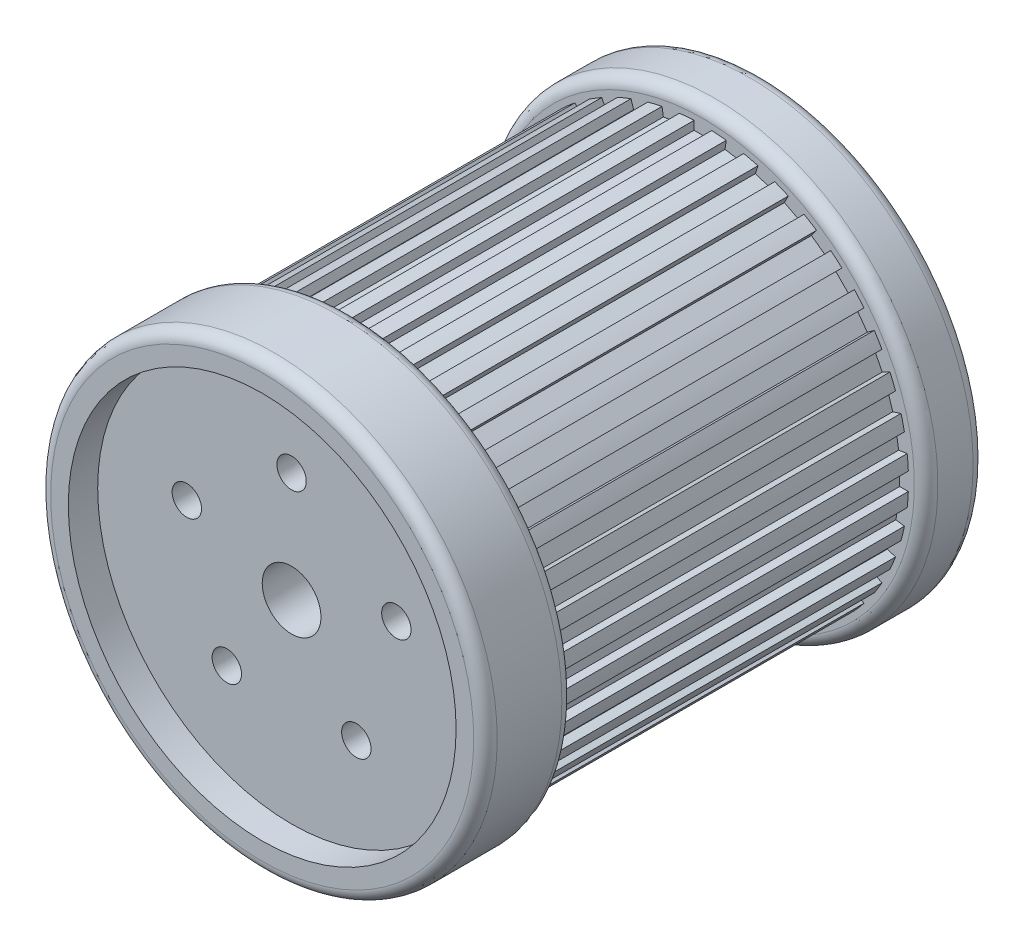
SolidWorks part; units mm, degrees
ref_plane "Front Plane" through (0, 0, 0) normal (0, 0, 1) x (1, 0, 0)
ref_plane "Top Plane" through (0, 0, 0) normal (0, 1, 0) x (1, 0, 0)
ref_plane "Right Plane" through (0, 0, 0) normal (1, 0, 0) x (0, 0, -1)
sketch "Sketch1" plane through (0, 0, 0) normal (1, 0, 0) x (0, 0, -1)
  line L0 (-51.6456, 0) -> (51.6456, 0) construction
  line L1 (-52.5, 35) -> (-52.5, -35) construction
  line L2 (-42.5, 25) -> (42.5, 25) construction
  line L3 (-42.5, 25) -> (-42.5, -25) construction
  line L4 (-42.5, -25) -> (42.5, -25) construction
  line L5 (42.5, 25) -> (42.5, -25) construction
  line L6 (-42.5, 25) -> (42.5, -25) construction
  line L7 (-42.5, -25) -> (42.5, 25) construction
  line L8 (-52.5, -35) -> (52.5, -35) construction
  line L9 (52.5, 35) -> (52.5, -35) construction
  line L10 (-52.5, 35) -> (52.5, 35) construction
  line L11 (-27.5, 0) -> (-27.5, -35)
  line L12 (-27.5, -35) -> (52.5, -35)
  line L13 (-27.5, 0) -> (-17.5, 0)
  line L14 (-17.5, 0) -> (-17.5, -25)
  line L15 (-17.5, -25) -> (52.5, -25)
  line L16 (52.5, -25) -> (52.5, -35)
  point P0 (0, 0)
  point P4 (0, 0)
  dimension "D2" = 50
  dimension "D3" = 80
  dimension "D4" = 50
  dimension "D5" = 85
  dimension "D1" = 10
revolve "Revolve1" add sketch "Sketch1" angle 360 about L0
sketch "Sketch2" plane through (0, 0, 17.5) normal (0, 0, -1) x (-1, 0, 0)
  circle A0 centre (0, 0) radius 5
  circle A1 centre (0, 0) radius 18.75 construction
  circle A2 centre (0, 18.75) radius 2.5
  circle A3 centre (17.8323, 5.7941) radius 2.5
  circle A4 centre (11.021, -15.1691) radius 2.5
  circle A5 centre (-11.021, -15.1691) radius 2.5
  circle A6 centre (-17.8323, 5.7941) radius 2.5
  point P16 (0, 0)
  point P17 (-0.5161, 0.375)
  dimension "D1" = 5
  dimension "D2" = 10
  dimension "D3" = 37.5
  dimension "D4" = 5
extrude "Cut-Extrude1" cut sketch "Sketch2" against normal blind 10
fillet "Fillet1" radius 3 2 edges at (25, 0, -52.5) (35, 0, -52.5)
sketch "Sketch3" plane through (0, 0, -52.5) normal (0, 0, -1) x (-1, 0, 0)
  line L1 (-1.5, 36.5) -> (1.5, 36.5)
  line L2 (-1.5, 36.5) -> (-1.5, 33.5)
  line L3 (-1.5, 33.5) -> (1.5, 33.5)
  line L4 (1.5, 36.5) -> (1.5, 33.5)
  line L5 (-1.5, 36.5) -> (1.5, 33.5) construction
  line L6 (-1.5, 33.5) -> (1.5, 36.5) construction
  circle A0 centre (0, 0) radius 35 construction
  point P0 (0, 35)
  dimension "D1" = 3
  dimension "D2" = 3
extrude "Cut-Extrude2" cut sketch "Sketch3" against normal blind 70
sketch "Sketch4" plane through (0, 0, 27.5) normal (0, 0, 1) x (1, 0, 0)
  circle A0 centre (0, 0) radius 38
  circle A1 centre (0, 0) radius 35
  circle A2 centre (0, 0) radius 35
  dimension "D1" = 0
  dimension "D2" = 3
extrude "Boss-Extrude2" add sketch "Sketch4" against normal up to surface (10 mm away) up to face at (0, 34.242, 17.5)
pattern_circular "CirPattern1" count 40 over 360 about axis through (0, 0, 0) along (0, 0, 1) of "Cut-Extrude2"
fillet "Fillet5" radius 2 1 edges at (-38, 0, 17.5)
sketch "Sketch5" plane through (0, 0, 27.5) normal (0, 0, 1) x (1, 0, 0)
  circle A0 centre (0, 0) radius 38 construction
  circle A1 centre (0, 0) radius 38
  circle A2 centre (0, 0) radius 33
  dimension "D1" = 5
extrude "Boss-Extrude4" add sketch "Sketch5" along normal blind 5
sketch "Sketch6" plane through (0, 0, -52.5) normal (0, 0, -1) x (-1, 0, 0)
  circle A0 centre (0, 0) radius 32 construction
  circle A1 centre (0, 0) radius 32
  circle A2 centre (0, 0) radius 38 construction
  circle A3 centre (0, 0) radius 38
extrude "Boss-Extrude5" add sketch "Sketch6" against normal blind 10
fillet "Fillet6" radius 2 3 edges at (-38, 0, -42.5) (-38, 0, -52.5) (38, 0, 32.5)
